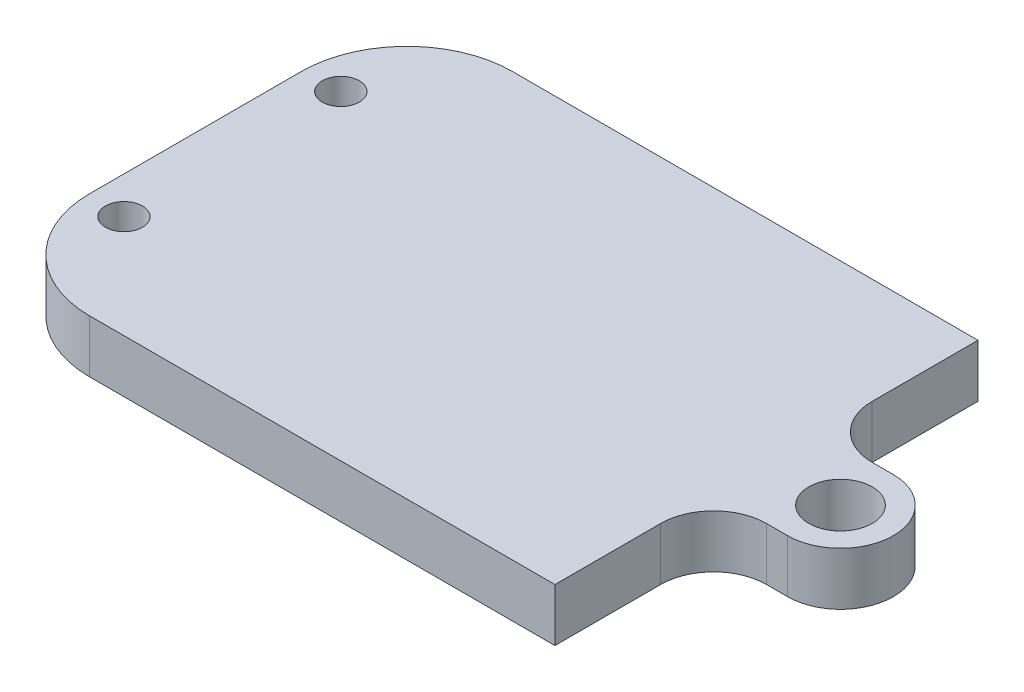
SolidWorks part; units mm, degrees
ref_plane "Front Plane" through (0, 0, 0) normal (0, 0, 1) x (1, 0, 0)
ref_plane "Top Plane" through (0, 0, 0) normal (0, 1, 0) x (1, 0, 0)
ref_plane "Right Plane" through (0, 0, 0) normal (1, 0, 0) x (0, 0, -1)
sketch "Sketch1" plane through (0, 0, 0) normal (0, 1, 0) x (1, 0, 0)
  line L2 (-26.5, 20) -> (26.5, 20)
  line L3 (-26.5, 20) -> (-26.5, -20)
  line L4 (-26.5, -20) -> (26.5, -20)
  line L5 (26.5, 20) -> (26.5, -20)
  line L6 (-26.5, 20) -> (26.5, -20) construction
  line L7 (-26.5, -20) -> (26.5, 20) construction
  point P1 (0, 0)
  dimension "D1" = 53
  dimension "D2" = 40
extrude "Boss-Extrude1" add sketch "Sketch1" along normal blind 5
sketch "Sketch2" plane through (0, 5, 0) normal (0, 1, 0) x (1, 0, 0)
  line L0 (-26.5, 20) -> (-26.5, -20) construction
  circle A0 centre (-24, 10.2521) radius 1.75
  circle A1 centre (-24, -10.2521) radius 1.75
  dimension "D1" = 3.5
  dimension "D3" = 3.5
  dimension "D2" = 2.5
  dimension "D4" = 2.5
  dimension "D5" = 10.2521
  dimension "10.252098mm" = 10.2521
extrude "Cut-Extrude1" cut sketch "Sketch2" against normal blind 5
sketch "Sketch3" plane through (-26.5, 0, 0) normal (-1, 0, 0) x (0, 0, 1)
  line L1 (-20, 5) -> (20, 5)
  line L2 (-20, 5) -> (-20, 0)
  line L3 (-20, 0) -> (20, 0)
  line L4 (20, 5) -> (20, 0)
extrude "Boss-Extrude2" add sketch "Sketch3" along normal blind 1
fillet "Fillet2" radius 10 2 edges at (-27.5, 2.5, 20) (-27.5, 2.5, -20)
sketch "Sketch4" plane through (0, 5, 0) normal (0, 1, 0) x (1, 0, 0)
  line L1 (26.5, 5) -> (33.5, 5)
  line L2 (26.5, -20) -> (26.5, 20) construction
  line L3 (26.5, -5) -> (33.5, -5)
  line L4 (26.5, 5) -> (26.5, -5)
  arc A0 (33.5, 5) -> (33.5, -5) centre (33.5, 0) cw
  point P7 (26.5, 0)
  dimension "D3" = 5
  dimension "D1" = 7
  dimension "D2" = 7
  dimension "D4" = 0
  dimension "D5" = 10
extrude "Boss-Extrude3" add sketch "Sketch4" against normal up to surface (5 mm away) up to face at (-24, 0, -8.5021)
sketch "Sketch5" plane through (0, 5, 0) normal (0, 1, 0) x (1, 0, 0)
  circle A0 centre (33.5, 0) radius 3
  arc A1 (33.5, -5) -> (33.5, 5) centre (33.5, 0) ccw construction
  point P5 (38.5, 0)
  dimension "D3" = 6
  dimension "D1" = 5
  dimension "D2" = 5
extrude "Cut-Extrude2" cut sketch "Sketch5" against normal blind 7
fillet "Fillet3" radius 5 2 edges at (26.5, 2.5, 5) (26.5, 2.5, -5)
